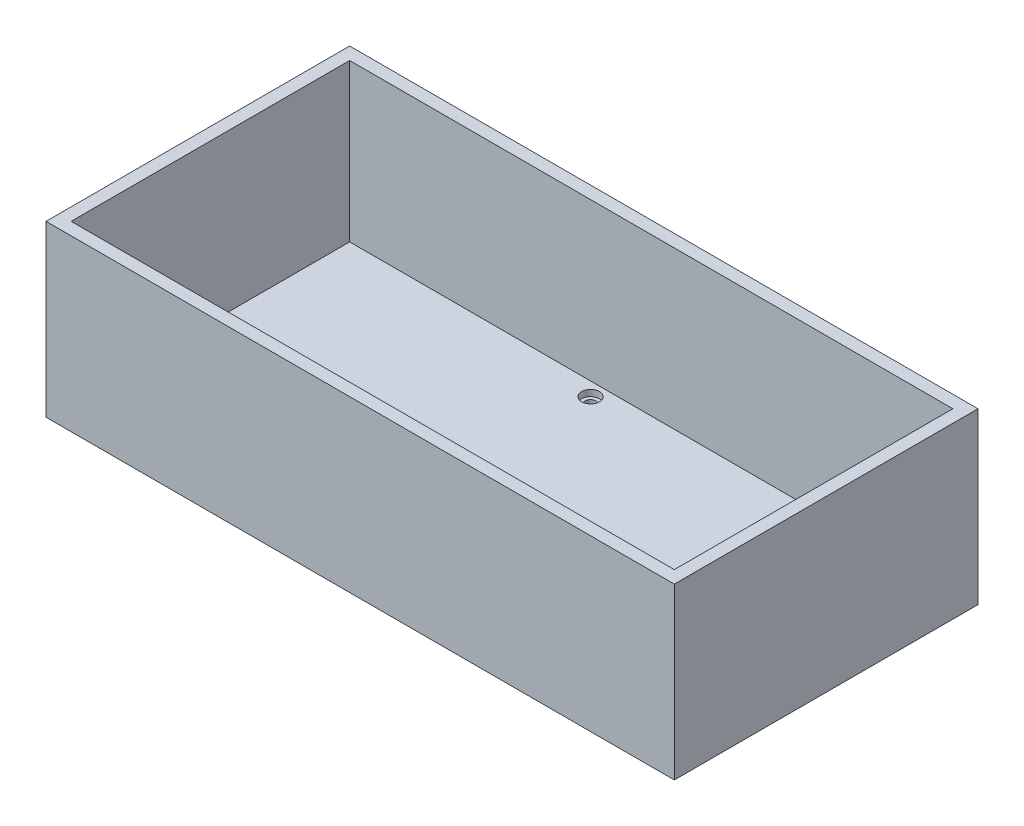
SolidWorks part; units mm, degrees
material "Polypropylene"
ref_plane "正面" through (0, 0, 0) normal (0, 0, 1) x (1, 0, 0)
ref_plane "平面" through (0, 0, 0) normal (0, 1, 0) x (1, 0, 0)
ref_plane "右側面" through (0, 0, 0) normal (1, 0, 0) x (0, 0, -1)
sketch "ｽｹｯﾁ1" plane through (0, 0, 0) normal (0, 1, 0) x (1, 0, 0)
  line L1 (-150, 72.5) -> (150, 72.5)
  line L2 (-150, 72.5) -> (-150, -72.5)
  line L3 (-150, -72.5) -> (150, -72.5)
  line L4 (150, 72.5) -> (150, -72.5)
  line L5 (-150, 72.5) -> (150, -72.5) construction
  line L6 (-150, -72.5) -> (150, 72.5) construction
  point P0 (0, 0)
  dimension "D1" = 300
  dimension "D2" = 145
extrude "ﾎﾞｽ - 押し出し1" add sketch "ｽｹｯﾁ1" along normal blind 81
shell "ｼｪﾙ1" thickness 6
sketch "ｽｹｯﾁ2" plane through (0, 6, 0) normal (0, 1, 0) x (1, 0, 0)
  line L0 (140, 72.5) -> (140, -72.5) construction
  line L1 (150, 72.5) -> (-150, 72.5) construction
  line L2 (-150, -72.5) -> (150, -72.5) construction
  line L3 (140, -72.5) -> (-22.5, -72.5) construction
  line L4 (-22.5, -72.5) -> (-22.5, 72.5) construction
  line L6 (150, -72.5) -> (150, 72.5) construction
  line L7 (-22.5, 0) -> (140, 0) construction
  line L8 (58.75, 72.5) -> (58.75, -72.5) construction
  circle A0 centre (140, 60) radius 2.55
  circle A1 centre (140, -60) radius 2.55
  circle A2 centre (-22.5, -60) radius 2.55
  circle A3 centre (-22.5, 60) radius 2.55
  point P18 (58.75, 0)
  dimension "D3" = 5.1
  dimension "D1" = 162.5
  dimension "D2" = 10
  dimension "D4" = 60
extrude "ｶｯﾄ - 押し出し1" cut sketch "ｽｹｯﾁ2" against normal through all
sketch "ｽｹｯﾁ3" plane through (0, 6, 0) normal (0, 1, 0) x (1, 0, 0)
  circle A0 centre (140, 60) radius 4.25
  circle A1 centre (-22.5, 60) radius 4.25
  circle A2 centre (-22.5, -60) radius 4.25
  circle A3 centre (140, -60) radius 4.25
  dimension "D1" = 8.5
extrude "ｶｯﾄ - 押し出し2" cut sketch "ｽｹｯﾁ3" against normal blind 3
